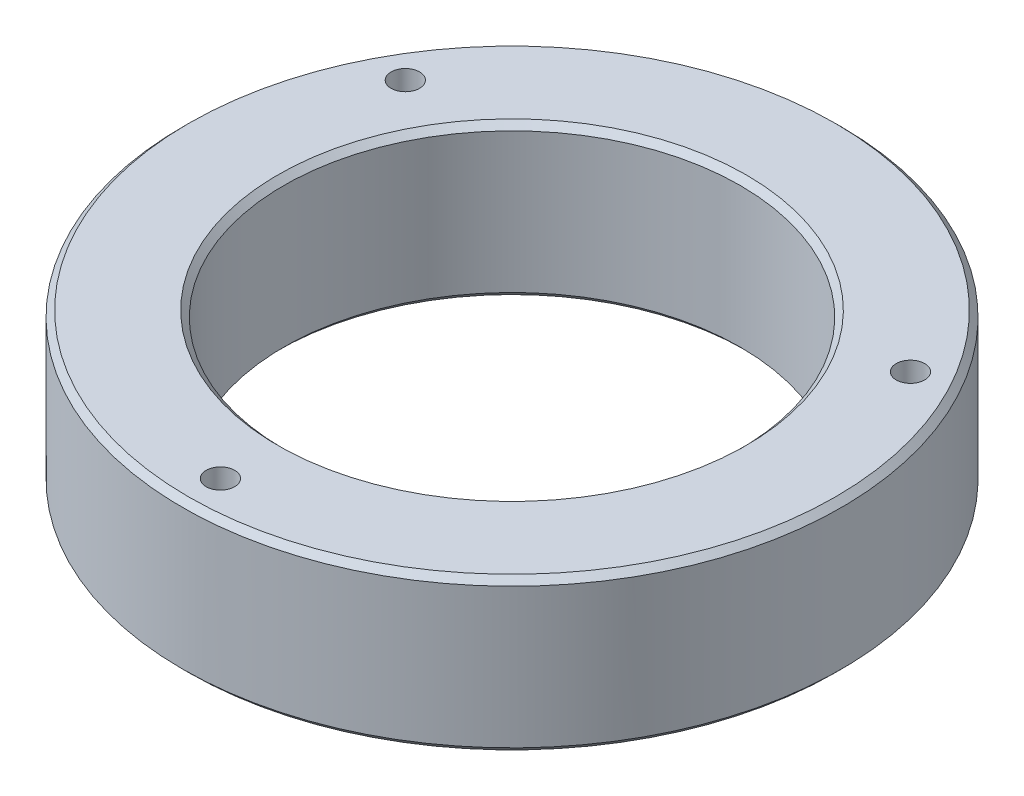
SolidWorks part; units mm, degrees
ref_plane "Front Plane" through (0, 0, 0) normal (1, 0, 0) x (0, 1, 0)
ref_plane "Top Plane" through (0, 0, 0) normal (0, 0, 1) x (0, 1, 0)
ref_plane "Right Plane" through (0, 0, 0) normal (0, 1, 0) x (-1, 0, 0)
sketch "Sketch1" plane through (0, 0, 0) normal (0, 0, 1) x (0, 1, 0)
  line L0 (-19.05, 82.5246) -> (19.05, 82.5246)
  line L1 (19.05, 82.5246) -> (19.05, 57.15)
  line L2 (19.05, 57.15) -> (-19.05, 57.15)
  line L3 (-19.05, 57.15) -> (-19.05, 82.5246)
  line L4 (-44.45, 0) -> (44.45, 0) construction
  dimension "D1" = 38.1
  dimension "D2" = 25.3746
  dimension "D3" = 82.5246
revolve "Revolve1" add sketch "Sketch1" angle 360 about L4
chamfer "Chamfer1" distance 1.524 angle 45 4 edges at (0, 19.05, -57.15) (0, -19.05, -57.15) (0, 19.05, -82.5246) (0, -19.05, -82.5246)
hole_wizard "CBORE for 1/4 Socket Head Cap Screw1" positions "Sketch3" profile "Sketch2" counterbore size "1/4" standard "ANSI Inch"
sketch "Sketch3" plane through (0, -19.05, 0) normal (0, -1, 0) x (-1, 0, 0)
  circle A0 centre (0, 0.0068) radius 73.0318 construction
  circle A1 centre (0, 0) radius 58.674 construction
  point P0 (0, -73.025)
  point P1 (-63.246, 36.5252)
  point P3 (63.246, 36.5252)
  dimension "D1" = 146.0637
  dimension "D2" = 63.246
  dimension "D3" = 63.246
  dimension "D4" = 0.0068
  dimension "D5" = 36.5252
  dimension "D6" = 73.025
sketch "Sketch2" plane through (0, -19.05, 73.025) normal (1, 0, 0) x (0, 0, -1)
  line L0 (0, 0) -> (0, 40.2443)
  line L1 (0, 40.2443) -> (3.5687, 38.1)
  line L2 (3.5687, 38.1) -> (3.5687, 9.652)
  line L3 (3.5687, 9.652) -> (5.5626, 9.652)
  line L4 (5.5626, 9.652) -> (5.5626, 0)
  line L5 (5.5626, 0) -> (0, 0)
  line L10 (0, 40.2443) -> (-3.5687, 38.1) construction
  line L11 (0, -6.35) -> (0, 107.95) construction
  dimension "Hole Dia." = 7.1374
  dimension "Hole Depth" = 38.1
  dimension "C'Bore Dia." = 11.1252
  dimension "C'Bore Depth" = 9.652
  dimension "Drill Angle" = 118
hole_wizard "3/8-16 Tapped Hole2" positions "Sketch7" profile "Sketch6" tap size "3/8-16" standard "ANSI Inch"
sketch "Sketch7" plane through (0, -19.05, 0) normal (0, -1, 0) x (-1, 0, 0)
  circle A0 centre (0, -73.025) radius 5.5626 construction
  point P0 (-69.85, 0)
  point P1 (69.85, 0)
  dimension "D1" = 69.85
  dimension "D2" = 69.85
  dimension "D3" = 73.025
  dimension "D4" = 73.025
sketch "Sketch6" plane through (69.85, -19.05, 0) normal (1, 0, 0) x (0, 0, -1)
  line L0 (0, 0) -> (0, 27.7847)
  line L1 (0, 27.7847) -> (3.9687, 25.4)
  line L2 (3.9687, 25.4) -> (3.9687, 0)
  line L5 (3.9687, 0) -> (0, 0)
  line L10 (0, 27.7847) -> (-3.9687, 25.4) construction
  line L11 (0, -6.35) -> (0, 107.95) construction
  dimension "Tap Drill Dia." = 7.9375
  dimension "Tap Drill Depth" = 25.4
  dimension "Drill Angle" = 118
cosmetic thread "Hole Thread3"
cosmetic thread "Hole Thread4"
